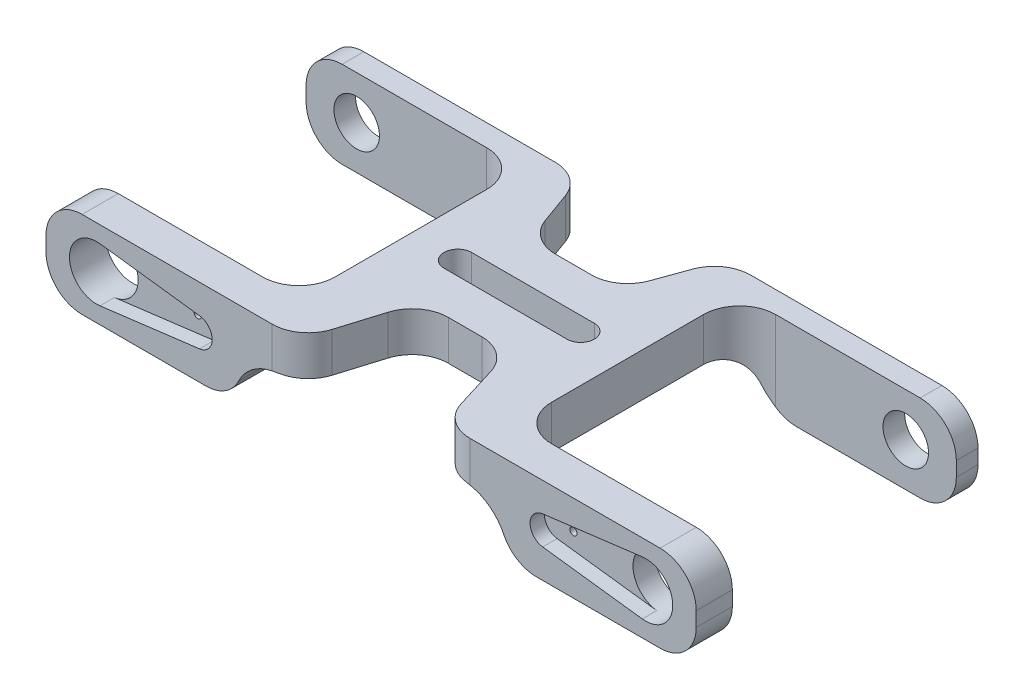
SolidWorks part; units mm, degrees
ref_plane "Ön Düzlem" through (0, 0, 0) normal (0, 0, 1) x (1, 0, 0)
ref_plane "Üst Düzlem" through (0, 0, 0) normal (0, 1, 0) x (1, 0, 0)
ref_plane "Sağ Düzlem" through (0, 0, 0) normal (1, 0, 0) x (0, 0, -1)
sketch "Çizim1" plane through (0, 0, 0) normal (0, 0, 1) x (1, 0, 0)
  line L0 (-45, 0) -> (45, 0) construction
  line L1 (-45, -10) -> (-15, -10) construction
  line L2 (-45, 10) -> (-15, 10) construction
  line L3 (-15, -5) -> (15, -5)
  line L4 (-15, 5) -> (15, 5)
  line L5 (-15, 10) -> (-15, -10) construction
  line L6 (0, 10) -> (0, -10) construction
  line L7 (-45, 5) -> (-15, 5)
  line L8 (-15, -5) -> (-45, -5)
  line L9 (-45, 10) -> (45, 10) construction
  line L10 (15, 5) -> (15, -5)
  line L11 (-45, -10) -> (45, -10) construction
  line L12 (-45, 5) -> (45, 5) construction
  line L13 (-45, -5) -> (45, -5) construction
  line L14 (15, -5) -> (45, -5)
  line L15 (15, 5) -> (45, 5)
  line L16 (-15, 5) -> (-15, -5)
  arc A0 (-45, 5) -> (-45, -5) centre (-45, 0) ccw
  arc A1 (45, 5) -> (45, -5) centre (45, 0) cw
  circle A2 centre (-45, 0) radius 2.5
  circle A3 centre (45, 0) radius 2.5
  point P3 (0, 0)
  point P25 (0, -5)
  point P30 (0, 5)
  dimension "D5" = 5
  dimension "D1" = 90
  dimension "D6" = 30
  dimension "D2" = 10
  dimension "D3" = 10
  dimension "D4" = 5
sketch "Çizim2" plane through (0, 0, 0) normal (0, 1, 0) x (1, 0, 0)
  line L0 (-45, -15.5) -> (-45, -20.5)
  line L1 (-45, -20.5) -> (-10, -20.5)
  line L3 (-6.0226, -7.5) -> (0, -7.5)
  line L5 (-45, -15.5) -> (-20, -15.5)
  line L6 (-15, -10.5) -> (-15, 10.5)
  line L7 (-10, 18.5) -> (-6.0226, 7.5)
  line L8 (-20, 15.5) -> (-45, 15.5)
  line L9 (-45, 15.5) -> (-45, 18.5)
  line L10 (-45, 18.5) -> (-10, 18.5)
  line L12 (-6.0226, 7.5) -> (0, 7.5)
  line L14 (-55.6176, 0) -> (71.7186, 0) construction
  line L15 (0, 7.5) -> (0, -7.5)
  line L16 (-10, -20.5) -> (-6.0226, -7.5)
  arc A4 (-20, -15.5) -> (-15, -10.5) centre (-20, -10.5) ccw
  arc A5 (-15, 10.5) -> (-20, 15.5) centre (-20, 10.5) ccw
  point P6 (0, 0)
  point P16 (-15, 0)
  point P24 (-10, -20.5)
  point P29 (-15, -15.5)
  point P32 (-15, 15.5)
  dimension "D9" = 5
  dimension "D1" = 35
  dimension "D2" = 31
  dimension "D3" = 30
  dimension "D4" = 5
  dimension "D5" = 3
  dimension "D6" = 15
  dimension "D10" = 15
extrude "Yükseklik-Ekstrüzyon1" add sketch "Çizim2" along normal blind 12
sketch "Çizim3" plane through (0, 0, 20.5) normal (0, 0, 1) x (1, 0, 0)
  line L0 (-45, 6) -> (-38, 6) construction
  line L1 (-45, 12) -> (-45, 0) construction
  circle A0 centre (-38, 6) radius 3.15
  dimension "D2" = 6.3
  dimension "D1" = 7
extrude "Kes-Ekstrüzyon1" cut sketch "Çizim3" against normal through all
sketch "Çizim5" plane through (0, 0, 20.5) normal (0, 0, 1) x (1, 0, 0)
  line L0 (-37.5312, 2.2794) -> (-23.75, 4.0157)
  line L3 (-23.75, 7.9843) -> (-37.5312, 9.7206)
  line L4 (-23.75, 7.9843) -> (-36.3324, 9.5695) construction
  line L5 (-42.608, 1.6398) -> (-23.75, 4.0157) construction
  line L6 (-38, 6) -> (-24, 6) construction
  line L9 (-42.633, 1.8382) -> (-23.775, 4.2141) construction
  line L10 (-23.775, 7.7859) -> (-36.3574, 9.3711) construction
  circle A0 centre (-38, 6) radius 2.425
  circle A2 centre (-38, 6) radius 3.75
  arc A3 (-23.75, 4.0157) -> (-23.75, 7.9843) centre (-24, 6) ccw
  arc A4 (-23.75, 4.0157) -> (-23.75, 7.9843) centre (-24, 6) ccw construction
  arc A5 (-23.775, 4.2141) -> (-23.775, 7.7859) centre (-24, 6) ccw construction
  circle A9 centre (-38, 6) radius 2.625 construction
  point P36 (-24, 6)
  dimension "D2" = 7.5
  dimension "D4" = 2
  dimension "D3" = 14
  dimension "D1" = 0.2
extrude "Kes-Ekstrüzyon2" cut sketch "Çizim5" against normal blind 2 contours L0 A3 L3 A2
sketch "Çizim8" plane through (0, 0, 20.5) normal (0, 0, 1) x (1, 0, 0)
  circle A0 centre (-38, 6) radius 3.75
  dimension "D1" = 7.5
extrude "Kes-Ekstrüzyon5" cut sketch "Çizim8" against normal up to next
sketch "Çizim6" plane through (0, 0, 18.5) normal (0, 0, 1) x (1, 0, 0)
  circle A3 centre (-26, 6) radius 0.5
  circle A4 centre (-38, 6) radius 3.15 construction
  dimension "D1" = 12
  dimension "D2" = 1
extrude "Kes-Ekstrüzyon3" cut sketch "Çizim6" against normal up to next
mirror "Aynalama1" about plane through (0, 12, -7.5) normal (-1, 0, 0) of "Kes-Ekstrüzyon3", "Kes-Ekstrüzyon2", "Yükseklik-Ekstrüzyon1", "Kes-Ekstrüzyon1", "Kes-Ekstrüzyon5"
sketch "Çizim7" plane through (0, 0, 0) normal (0, 0, 1) x (1, 0, 0)
  line L0 (-12.5, 0) -> (12.5, 0) construction
  line L1 (-12.5, 6.5) -> (12.5, 6.5)
  line L2 (-12.5, -6.5) -> (12.5, -6.5)
  line L3 (6.0226, 0) -> (-6.0226, 0) construction
  arc A0 (-12.5, 6.5) -> (-12.5, -6.5) centre (-12.5, 0) ccw
  arc A1 (12.5, -6.5) -> (12.5, 6.5) centre (12.5, 0) ccw
  point P2 (0, 0)
  dimension "D1" = 13
  dimension "D2" = 25
extrude "Kes-Ekstrüzyon4" cut sketch "Çizim7" against normal mid plane 42
fillet "Radyus1" radius 5 18 edges at (-19.4975, 0, -15.4747) (-45, 0, -17) (19.4975, 0, 15.4747) (-19.4975, 0, 15.4747) (-19, 0, 17.9495) (-19, 0, -16.9495) (-16.7585, 4.9107, -14.3069) (16.7585, 4.9107, -14.3069) (19, 0, 17.9495) (19, 0, -16.9495) (-45, 0, 18) (-45, 12, -17) (-45, 12, 18) (45, 12, -17) (45, 12, 18) (45, 0, 18) (45, 0, -17) (19.4975, 0, -15.4747)
sketch "Sketch1" plane through (0, 12, 0) normal (0, 1, 0) x (1, 0, 0)
  line L0 (-10.6973, 3.0009) -> (-5.0379, 11.2453) construction
  line L1 (-12.3462, 4.1327) -> (-6.6868, 12.3772)
  line L2 (-9.0484, 1.869) -> (-3.389, 10.1134)
  line L3 (-9.7097, -5.9522) -> (1.6091, 10.5367) construction
  line L4 (-11.3586, -4.8203) -> (-0.0398, 11.6686)
  line L5 (-8.0608, -7.084) -> (3.258, 9.4049)
  line L6 (-5.5544, -11.3825) -> (9.1601, 10.0531) construction
  line L7 (-7.2033, -10.2506) -> (7.5112, 11.185)
  line L8 (-3.9056, -12.5143) -> (10.8089, 8.9212)
  line L9 (2.7953, -10.3243) -> (9.5866, -0.4309) construction
  line L10 (1.1464, -9.1924) -> (7.9377, 0.701)
  line L11 (4.4442, -11.4561) -> (11.2355, -1.5628)
  arc A0 (-12.3462, 4.1327) -> (-9.0484, 1.869) centre (-10.6973, 3.0009) ccw
  arc A1 (-3.389, 10.1134) -> (-6.6868, 12.3772) centre (-5.0379, 11.2453) ccw
  arc A2 (-11.3586, -4.8203) -> (-8.0608, -7.084) centre (-9.7097, -5.9522) ccw
  arc A3 (3.258, 9.4049) -> (-0.0398, 11.6686) centre (1.6091, 10.5367) ccw
  arc A4 (-7.2033, -10.2506) -> (-3.9056, -12.5143) centre (-5.5544, -11.3825) ccw
  arc A5 (10.8089, 8.9212) -> (7.5112, 11.185) centre (9.1601, 10.0531) ccw
  arc A6 (1.1464, -9.1924) -> (4.4442, -11.4561) centre (2.7953, -10.3243) ccw
  arc A7 (11.2355, -1.5628) -> (7.9377, 0.701) centre (9.5866, -0.4309) ccw
  point P2 (-7.8676, 7.1231)
  point P8 (-4.0503, 2.2923)
  point P15 (1.8028, -0.6647)
  point P23 (6.191, -5.3776)
  dimension "D1" = 2
  dimension "D2" = 10
  dimension "D3" = 20
  dimension "D4" = 26
  dimension "D5" = 12
extrude "Cut-Extrude1" [suppressed] cut sketch "Sketch1" against normal blind 10
fillet "Fillet1" radius 5 8 edges at (10, 9.25, 20.5) (6.0226, 9.25, 7.5) (-10, 9.25, 20.5) (-6.0226, 9.25, 7.5) (10, 9.25, -18.5) (6.0226, 9.25, -7.5) (-10, 9.25, -18.5) (-6.0226, 9.25, -7.5)
sketch "Sketch2" plane through (0, 12, 0) normal (0, 1, 0) x (1, 0, 0)
  line L0 (8.5, 0) -> (-8.5, 0) construction
  line L1 (8.5, -1.9) -> (-8.5, -1.9)
  line L2 (8.5, 1.9) -> (-8.5, 1.9)
  arc A0 (8.5, -1.9) -> (8.5, 1.9) centre (8.5, 0) ccw
  arc A1 (-8.5, 1.9) -> (-8.5, -1.9) centre (-8.5, 0) ccw
  point P2 (0, 0)
  dimension "D1" = 1.9
  dimension "D2" = 17
extrude "Cut-Extrude2" cut sketch "Sketch2" against normal blind 10
